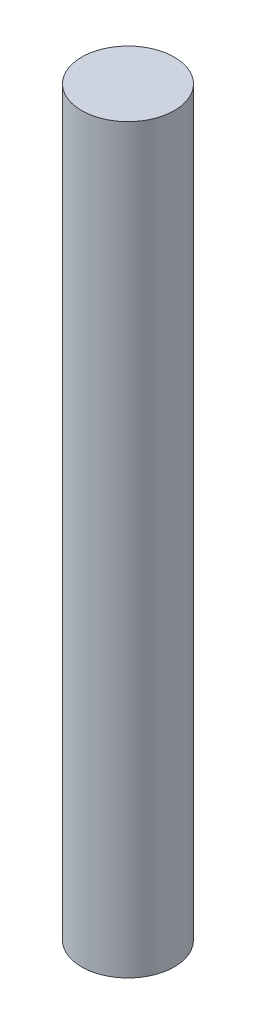
SolidWorks part; units mm, degrees
material "Oak"
ref_plane "Front" through (0, 0, 0) normal (0, 0, 1) x (1, 0, 0)
ref_plane "Top" through (0, 0, 0) normal (0, 1, 0) x (1, 0, 0)
ref_plane "Right" through (0, 0, 0) normal (1, 0, 0) x (0, 0, -1)
sketch "Sketch1" plane through (0, 0, 0) normal (0, 1, 0) x (1, 0, 0)
  circle A0 centre (0, 0) radius 5
  dimension "D1" = 10
extrude "Boss-Extrude1" add sketch "Sketch1" along normal blind 80
scale "Escala1" scale about centroid uniform scaling yes scale factor 0.2
